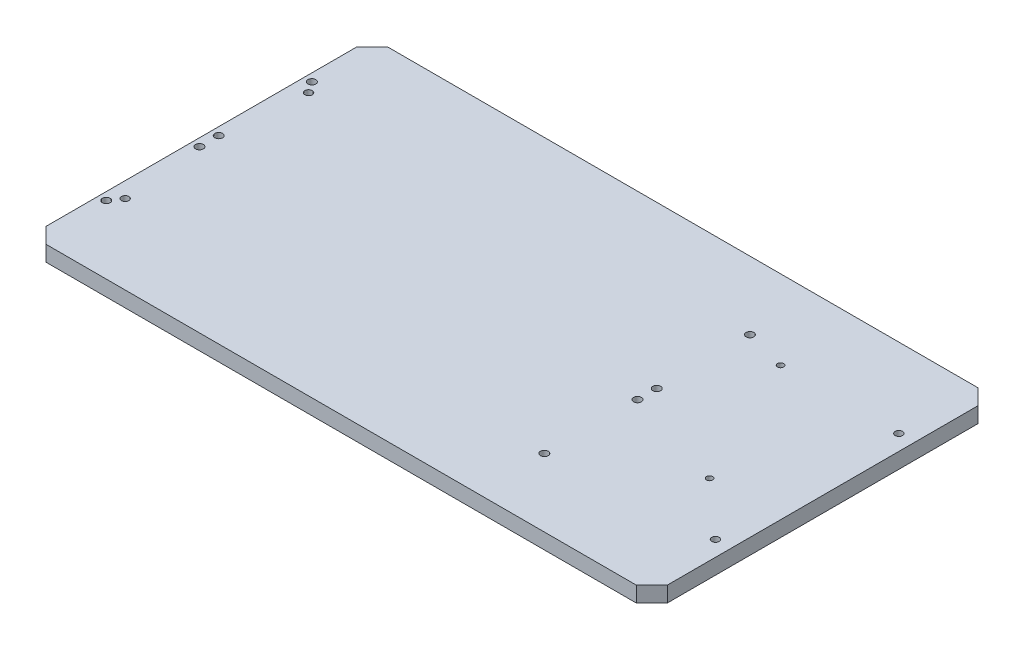
SolidWorks part; units mm, degrees
ref_plane "Front Plane" through (0, 0, 0) normal (0, 0, 1) x (1, 0, 0)
ref_plane "Top Plane" through (0, 0, 0) normal (0, 1, 0) x (1, 0, 0)
ref_plane "Right Plane" through (0, 0, 0) normal (1, 0, 0) x (0, 0, -1)
sketch "Sketch1" plane through (0, 0, 0) normal (0, 1, 0) x (1, 0, 0)
  line L0 (127, 139.7) -> (127, 0) construction
  line L1 (0, 69.85) -> (254, 69.85) construction
  line L2 (3.175, 116.332) -> (3.175, 23.368) construction
  line L3 (92.71, 69.85) -> (92.71, 115.1198) construction
  line L5 (254, 139.7) -> (0, 139.7)
  line L6 (254, 139.7) -> (254, 0)
  line L7 (254, 0) -> (0, 0)
  line L8 (0, 139.7) -> (0, 0)
  circle A0 centre (6.35, 107.3404) radius 1.5
  circle A1 centre (6.35, 32.3596) radius 1.5
  circle A2 centre (247.65, 107.3404) radius 1.5
  circle A3 centre (247.65, 32.3596) radius 1.5
  circle A4 centre (3.175, 73.787) radius 1.5875
  circle A5 centre (3.175, 65.913) radius 1.5875
  circle A6 centre (3.175, 27.813) radius 1.5875
  circle A7 centre (3.175, 111.887) radius 1.5875
  circle A8 centre (182.245, 27.813) radius 1.5875
  circle A9 centre (182.245, 65.913) radius 1.5875
  circle A10 centre (182.245, 73.787) radius 1.5875
  circle A11 centre (182.245, 111.887) radius 1.5875
  point P27 (3.175, 69.85)
  dimension "D4" = 3
  dimension "D6" = 3
  dimension "D9" = 3.175
  dimension "D10" = 3.175
  dimension "D11" = 3.175
  dimension "D12" = 3.175
  dimension "D1" = 139.7
  dimension "D2" = 254
  dimension "D3" = 120.65
  dimension "D5" = 120.65
  dimension "D7" = 37.4904
  dimension "D8" = 37.4904
  dimension "D13" = 38.1
  dimension "D14" = 38.1
  dimension "D15" = 92.964
  dimension "D16" = 4.445
  dimension "D17" = 4.445
  dimension "D18" = 3.175
  dimension "D19" = 89.535
extrude "Boss-Extrude1" add sketch "Sketch1" along normal blind 6.35
sketch "Sketch2" plane through (0, 6.35, 0) normal (0, 1, 0) x (1, 0, 0)
  line L0 (254, 139.7) -> (0, 139.7) construction
  line L1 (186.824, 112.305) -> (242.824, 112.305) construction
  line L2 (186.824, 112.305) -> (186.824, 27.305) construction
  line L3 (186.824, 27.305) -> (242.824, 27.305) construction
  line L4 (242.824, 112.305) -> (242.824, 27.305) construction
  line L5 (0, 0) -> (254, 0) construction
  line L8 (182.245, 111.887) -> (182.245, 123.249) construction
  line L9 (247.65, 107.3404) -> (247.65, 121.3229) construction
  line L10 (214.884, 40.4289) -> (214.884, 71.968) construction
  circle A0 centre (199.324, 107.305) radius 1.25
  circle A1 centre (224.824, 52.805) radius 1.25
  dimension "D3" = 2.5
  dimension "D6" = 2.5
  dimension "D11" = 27.94
  dimension "D1" = 85
  dimension "D2" = 56
  dimension "D4" = 5
  dimension "D5" = 12.5
  dimension "D7" = 18
  dimension "D8" = 25.5
  dimension "D9" = 27.395
  dimension "D10" = 27.305
  dimension "D12" = 32.766
extrude "Cut-Extrude1" cut sketch "Sketch2" against normal blind 6.35
chamfer "Chamfer1" distance 6.35 angle 45 4 edges at (0, 3.175, -139.7) (0, 3.175, 0) (254, 3.175, 0) (254, 3.175, -139.7)
